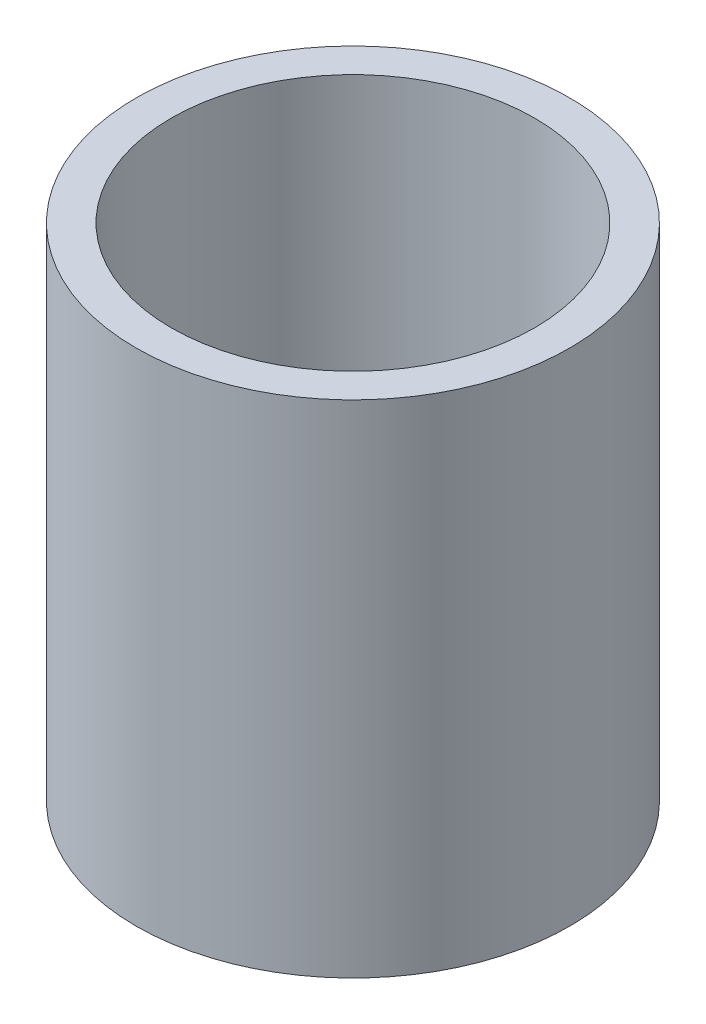
SolidWorks part; units mm, degrees
ref_plane "Front Plane" through (0, 0, 0) normal (0, 0, 1) x (1, 0, 0)
ref_plane "Top Plane" through (0, 0, 0) normal (0, 1, 0) x (1, 0, 0)
ref_plane "Right Plane" through (0, 0, 0) normal (1, 0, 0) x (0, 0, -1)
sketch "Sketch1" plane through (0, 0, 0) normal (0, 1, 0) x (1, 0, 0)
  circle A0 centre (0, 0) radius 30.3
  circle A1 centre (0, 0) radius 25.4
  dimension "D1" = 60.6
  dimension "D2" = 50.8
extrude "Boss-Extrude1" add sketch "Sketch1" along normal blind 70
